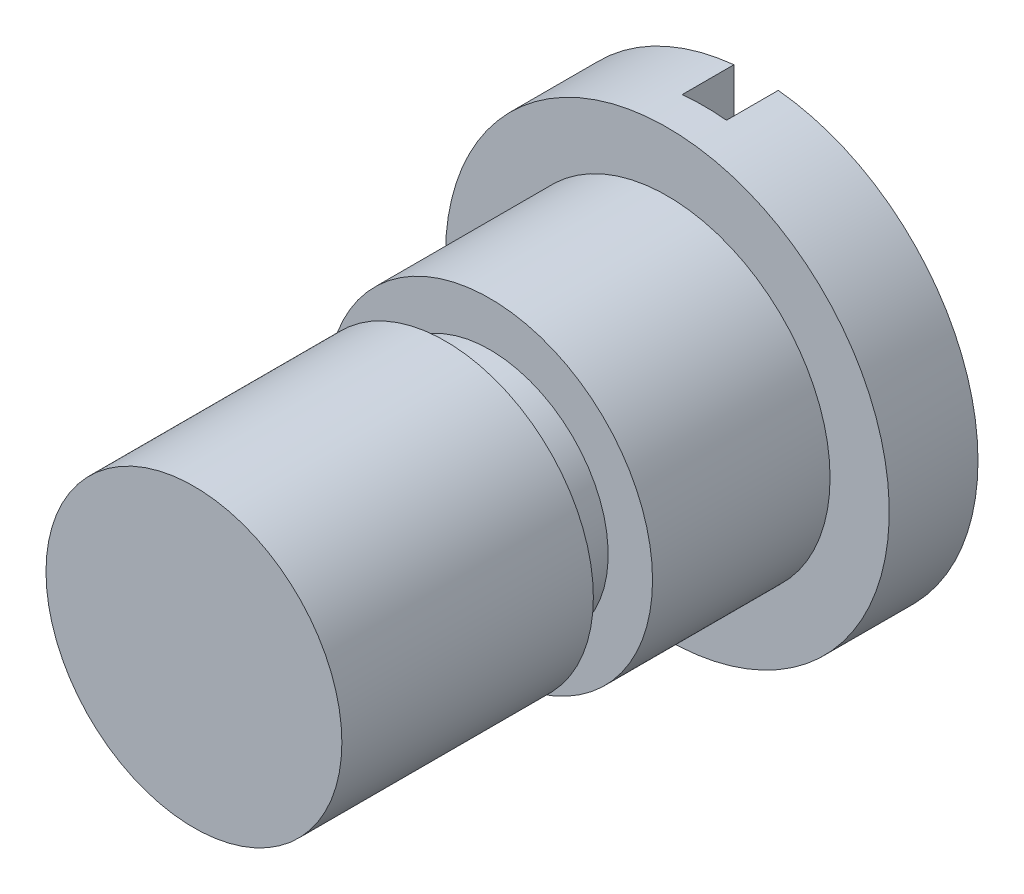
SolidWorks part; units mm, degrees
material "Stainless Steel (ferritic)"
ref_plane "Front Plane" through (0, 0, 0) normal (0, 0, 1) x (1, 0, 0)
ref_plane "Top Plane" through (0, 0, 0) normal (0, 1, 0) x (1, 0, 0)
ref_plane "Right Plane" through (0, 0, 0) normal (1, 0, 0) x (0, 0, -1)
sketch "Sketch1" plane through (0, 0, 0) normal (1, 0, 0) x (0, 0, -1)
  line L0 (0, 0) -> (0, 10)
  line L1 (0, 10) -> (17, 10)
  line L2 (17, 10) -> (17, 8)
  line L3 (17, 8) -> (20, 8)
  line L4 (20, 8) -> (20, 11)
  line L5 (20, 11) -> (32, 11)
  line L6 (32, 11) -> (32, 15)
  line L7 (32, 15) -> (38, 15)
  line L8 (38, 15) -> (38, 0)
  line L9 (38, 0) -> (0, 0)
  dimension "D1" = 15
  dimension "D2" = 11
  dimension "D3" = 10
  dimension "D4" = 8
  dimension "D5" = 17
  dimension "D6" = 3
  dimension "D7" = 6
  dimension "D8" = 38
revolve "Revolve1" add sketch "Sketch1" angle 360 about L9
sketch "Sketch2" plane through (0, 0, -38) normal (0, 0, -1) x (-1, 0, 0)
  line L0 (-1.5, 14.9248) -> (-1.5, -14.9248)
  line L1 (1.5, -14.9248) -> (1.5, 14.9248)
  circle A0 centre (0, 0) radius 15 construction
  arc A1 (-1.5, -14.9248) -> (1.5, -14.9248) centre (0, 0) ccw
  arc A2 (1.5, 14.9248) -> (-1.5, 14.9248) centre (0, 0) ccw
  dimension "D1" = 3
  dimension "D2" = 1.5
extrude "Cut-Extrude1" cut sketch "Sketch2" against normal blind 3.5
